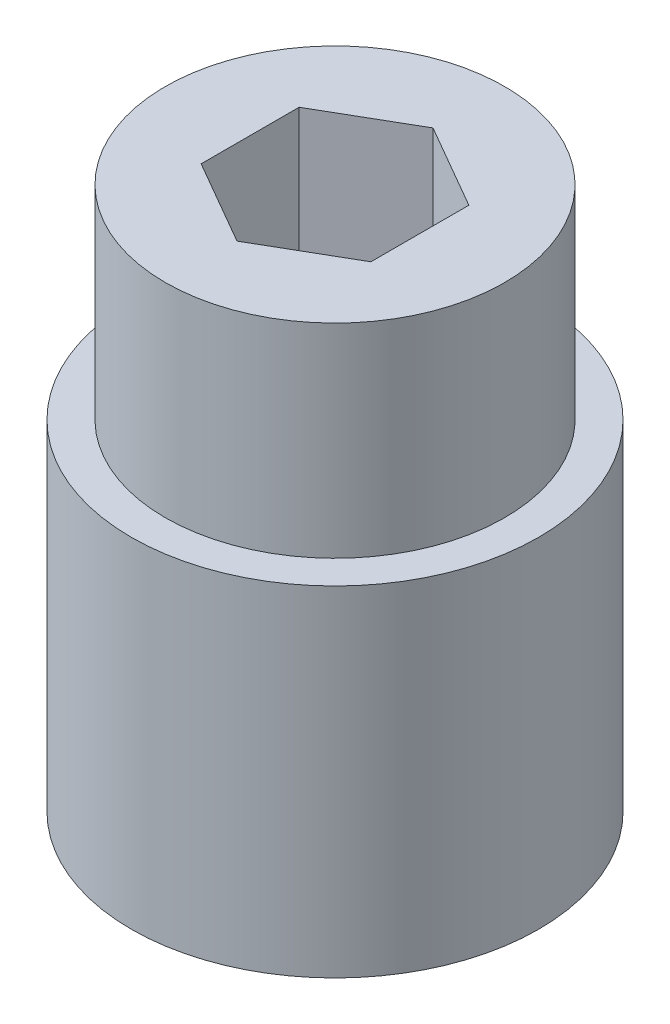
SolidWorks part; units mm, degrees
ref_plane "Front Plane" through (0, 0, 0) normal (0, 0, 1) x (1, 0, 0)
ref_plane "Top Plane" through (0, 0, 0) normal (0, 1, 0) x (1, 0, 0)
ref_plane "Right Plane" through (0, 0, 0) normal (1, 0, 0) x (0, 0, -1)
sketch "Sketch1" plane through (0, 0, 0) normal (0, 1, 0) x (1, 0, 0)
  circle A0 centre (0, 0) radius 7
  dimension "D1" = 14
extrude "Boss-Extrude1" add sketch "Sketch1" along normal blind 10
sketch "Sketch2" plane through (0, 10, 0) normal (0, 1, 0) x (1, 0, 0)
  circle A0 centre (0, 0) radius 5
  dimension "D1" = 10
extrude "Boss-Extrude2" add sketch "Sketch2" along normal blind 6
sketch "Sketch3" plane through (0, 16, 0) normal (0, 1, 0) x (1, 0, 0)
  line L1 (3.5, -1.4434) -> (3.5, 1.4434)
  line L2 (3.5, 1.4434) -> (1, 2.8868)
  line L3 (1, 2.8868) -> (-1.5, 1.4434)
  line L4 (-1.5, 1.4434) -> (-1.5, -1.4434)
  line L5 (-1.5, -1.4434) -> (1, -2.8868)
  line L6 (1, -2.8868) -> (3.5, -1.4434)
  circle A0 centre (1, 0) radius 2.5 construction
  dimension "D1" = 5
  dimension "D2" = 1
extrude "Cut-Extrude1" [suppressed] cut sketch "Sketch3" against normal through all
sketch "Sketch4" plane through (0, 16, 0) normal (0, 1, 0) x (1, 0, 0)
  line L1 (2.5, 1.4434) -> (0, 2.8868)
  line L2 (0, 2.8868) -> (-2.5, 1.4434)
  line L3 (-2.5, 1.4434) -> (-2.5, -1.4434)
  line L4 (-2.5, -1.4434) -> (0, -2.8868)
  line L5 (0, -2.8868) -> (2.5, -1.4434)
  line L6 (2.5, -1.4434) -> (2.5, 1.4434)
  circle A0 centre (0, 0) radius 2.5 construction
  dimension "D1" = 5
extrude "Cut-Extrude2" cut sketch "Sketch4" against normal through all
sketch "Sketch5" plane through (0, 10, 0) normal (0, 1, 0) x (1, 0, 0)
  circle A0 centre (0, 0) radius 6
  dimension "D1" = 12
extrude "Cut-Extrude3" cut sketch "Sketch5" against normal through all flip side to cut
equation "\"R_ROLL\"= 5mm"
equation "\"D_SUN\"= 80mm"
equation "\"NUM_ROLL\"= 16"
equation "\"RHO\"= 1mm"
equation "\"D_SHAFT\"= 15mm"
equation "\"D_OUTPUT\"= 40mm"
equation "\"NUM_OUT\"= 6"
equation "\"R_OUT_ROLL\"= 5mm"
